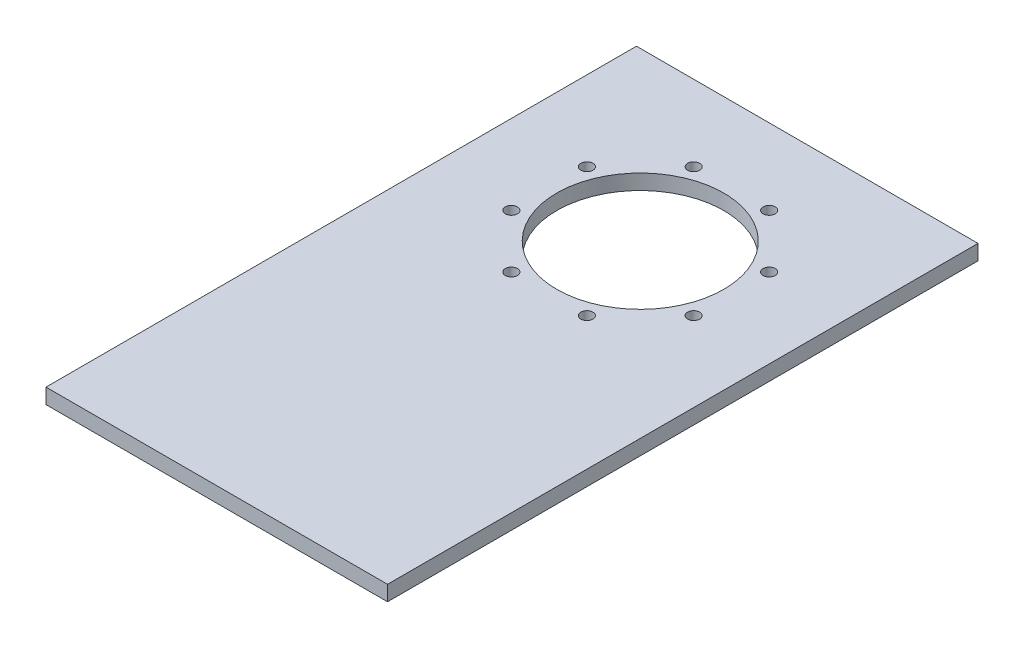
SolidWorks part; units mm, degrees
material "Plain Carbon Steel"
ref_plane "Front Plane" through (0, 0, 0) normal (0, 0, 1) x (1, 0, 0)
ref_plane "Top Plane" through (0, 0, 0) normal (0, 1, 0) x (1, 0, 0)
ref_plane "Right Plane" through (0, 0, 0) normal (1, 0, 0) x (0, 0, -1)
sketch "Sketch1" plane through (0, 0, 0) normal (0, 1, 0) x (1, 0, 0)
  line L1 (-112.5, -110) -> (112.5, -110)
  line L2 (-112.5, -110) -> (-112.5, 110)
  line L3 (-112.5, 110) -> (112.5, 110)
  line L4 (112.5, -110) -> (112.5, 110)
  line L5 (-112.5, -110) -> (112.5, 110) construction
  line L6 (-112.5, 110) -> (112.5, -110) construction
  circle A0 centre (0, 0) radius 55
  point P0 (0, 0)
  dimension "D3" = 110
  dimension "D1" = 220
  dimension "D2" = 225
extrude "Boss-Extrude1" add sketch "Sketch1" along normal blind 10
sketch "Sketch2" plane through (0, 0, 0) normal (0, 1, 0) x (1, 0, 0)
  line L0 (-24.8744, -60.0522) -> (0, 0) construction
  line L1 (0, -55) -> (0, 55) construction
  circle A0 centre (0, 0) radius 65 construction
  circle A1 centre (-24.8744, -60.0522) radius 4
  circle A2 centre (-60.0522, -24.8744) radius 4
  circle A3 centre (-60.0522, 24.8744) radius 4
  circle A4 centre (-24.8744, 60.0522) radius 4
  circle A5 centre (24.8744, 60.0522) radius 4
  circle A6 centre (60.0522, 24.8744) radius 4
  circle A7 centre (60.0522, -24.8744) radius 4
  circle A8 centre (24.8744, -60.0522) radius 4
  point P23 (0, 0)
  dimension "D1" = 130
  dimension "D2" = 8
  dimension "D3" = 22.5
extrude "Cut-Extrude1" cut sketch "Sketch2" along normal blind 10
sketch "Sketch3" plane through (0, 0, 110) normal (0, 0, 1) x (1, 0, 0)
  line L1 (-112.5, 10) -> (112.5, 10)
  line L2 (-112.5, 10) -> (-112.5, 0)
  line L3 (-112.5, 0) -> (112.5, 0)
  line L4 (112.5, 10) -> (112.5, 0)
extrude "Boss-Extrude2" add sketch "Sketch3" along normal blind 169
